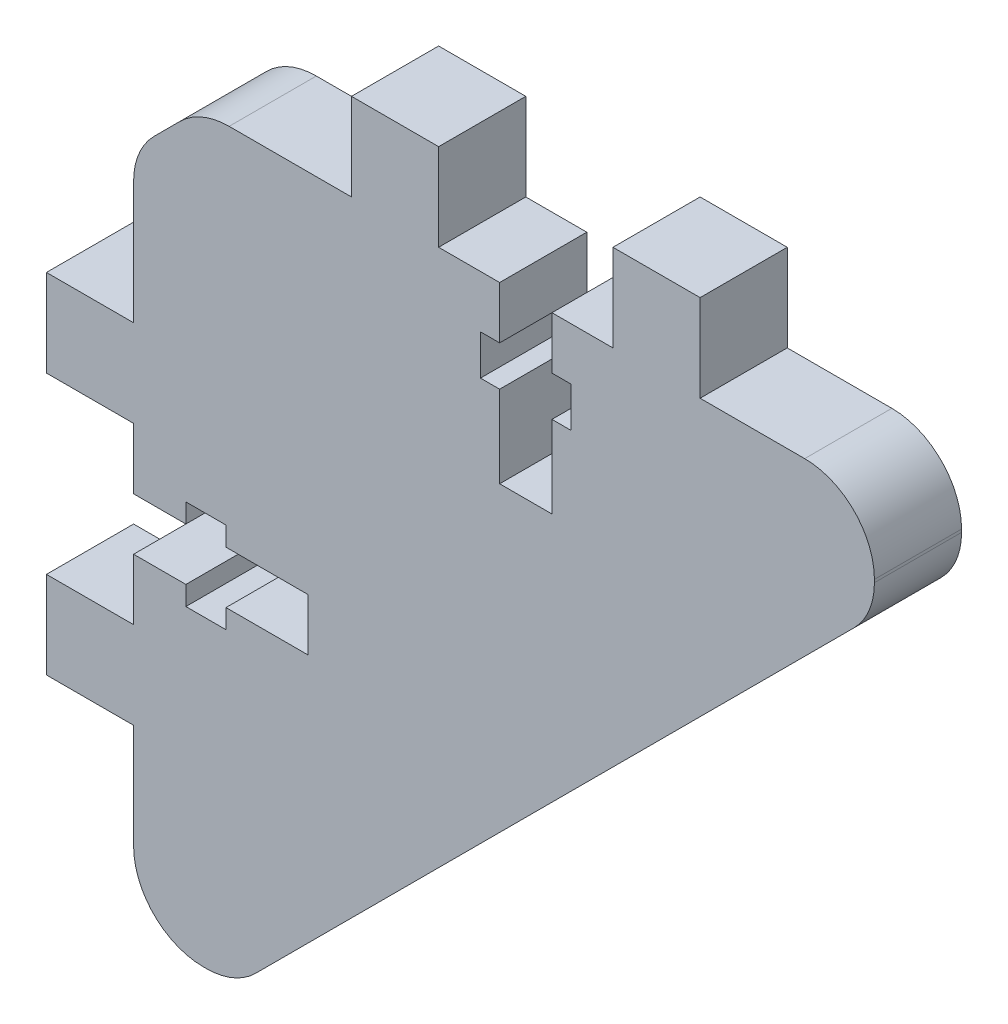
SolidWorks part; units mm, degrees
ref_plane "Front Plane" through (0, 0, 0) normal (0, 0, 1) x (1, 0, 0)
ref_plane "Top Plane" through (0, 0, 0) normal (0, 1, 0) x (1, 0, 0)
ref_plane "Right Plane" through (0, 0, 0) normal (1, 0, 0) x (0, 0, -1)
sketch "Sketch1" plane through (0, 0, 0) normal (0, 0, 1) x (1, 0, 0)
  line L0 (10.4817, -5) -> (43.5, -5)
  line L1 (47.5, -9) -> (47.5, -9.1655)
  line L2 (46.3284, -11.9939) -> (11.9939, -46.3284)
  line L3 (9.1655, -47.5) -> (9, -47.5)
  line L4 (5, -43.5) -> (5, -10.4817)
  line L5 (0, 18.5393) -> (0, -65.6726) construction
  line L6 (-18.1148, 0) -> (76.4115, 0) construction
  line L7 (6.1716, -7.6533) -> (7.6533, -6.1716)
  arc A0 (10.4817, -5) -> (7.6533, -6.1716) centre (10.4817, -9) ccw
  arc A1 (6.1716, -7.6533) -> (5, -10.4817) centre (9, -10.4817) ccw
  arc A2 (9, -47.5) -> (5, -43.5) centre (9, -43.5) cw
  arc A3 (11.9939, -46.3284) -> (9.1655, -47.5) centre (9.1655, -43.5) cw
  arc A4 (47.5, -9.1655) -> (46.3284, -11.9939) centre (43.5, -9.1655) cw
  arc A5 (47.5, -9) -> (43.5, -5) centre (43.5, -9) ccw
  point P0 (6.3905, -27.3056)
  line B0 (8, -24.9) -> (10.3, -24.9)
  line B1 (10.3, -29) -> (15, -29)
  line B2 (15, -26) -> (10.3, -26)
  line B3 (10.3, -24.9) -> (10.3, -26)
  line B4 (5, -27.5) -> (16.2208, -27.5) construction
  line B5 (5, -26) -> (5, -22.5)
  line B6 (0, -22.5) -> (0, -17.5)
  line B7 (0, -17.5) -> (5, -17.5)
  line B8 (0, -22.5) -> (5, -22.5)
  line B9 (5, -29) -> (5, -32.5)
  line B10 (5, -32.5) -> (0, -32.5)
  line B11 (0, -32.5) -> (0, -37.5)
  line B12 (0, -37.5) -> (5, -37.5)
  line B13 (5, -26) -> (5, -29) construction
  line B14 (5, -29) -> (8, -29)
  line B15 (10.3, -29) -> (10.3, -30.1)
  line B16 (8, -30.1) -> (8, -29)
  line B17 (15, -29) -> (15, -26)
  line B18 (8, -26) -> (8, -24.9)
  line B19 (10.3, -30.1) -> (8, -30.1)
  line B20 (8, -26) -> (5, -26)
  line B21 (15, -27.5) -> (5, -27.5) construction
  line B22 (30.1, -8) -> (30.1, -10.3)
  line B23 (26, -10.3) -> (26, -15)
  line B24 (29, -15) -> (29, -10.3)
  line B25 (30.1, -10.3) -> (29, -10.3)
  line B26 (27.5, -5) -> (27.5, -16.2208) construction
  line B27 (29, -5) -> (32.5, -5)
  line B28 (32.5, 0) -> (37.5, 0)
  line B29 (37.5, 0) -> (37.5, -5)
  line B30 (32.5, 0) -> (32.5, -5)
  line B31 (26, -5) -> (22.5, -5)
  line B32 (22.5, -5) -> (22.5, 0)
  line B33 (22.5, 0) -> (17.5, 0)
  line B34 (17.5, 0) -> (17.5, -5)
  line B35 (29, -5) -> (26, -5) construction
  line B36 (26, -5) -> (26, -8)
  line B37 (26, -10.3) -> (24.9, -10.3)
  line B38 (24.9, -8) -> (26, -8)
  line B39 (26, -15) -> (29, -15)
  line B40 (29, -8) -> (30.1, -8)
  line B41 (24.9, -10.3) -> (24.9, -8)
  line B42 (29, -8) -> (29, -5)
  line B43 (27.5, -15) -> (27.5, -5) construction
  dimension "D7" = 4
  dimension "D1" = 27.5
  dimension "D2" = 27.5
  dimension "D3" = 10
  dimension "D4" = 5
  dimension "D5" = 5
  dimension "D6" = 135
sketch_block_instance "Insert M3 plots ep 5mm-1"
sketch_block "Insert M3 plots ep 5mm" parameters "D1"=10, "D2"=5, "D3"=5
sketch_block_instance "Decoupe Insert M3-4"
sketch_block "Decoupe Insert M3" parameters "D1"=5.2, "D2"=3, "D3"=2.3, "D4"=3, "D5"=10
sketch_block_instance "Insert M3 plots ep 5mm-2"
extrude "Boss-Extrude1" add sketch "Sketch1" along normal blind 5 contours B42 B40 B22 B25 B24 B39 B23 B37 B41 B38 B36 L0 A0 L7 A1 L4 B20 B18 B0 B3 B2 B17 B1 B15 B19 B16 B14 A2 L3 A3 L2 A4 L1 A5 | B6 B8 L4 B7 | B33 B34 L0 B32 | B28 B30 L0 B29 | B11 B12 L4 B10
